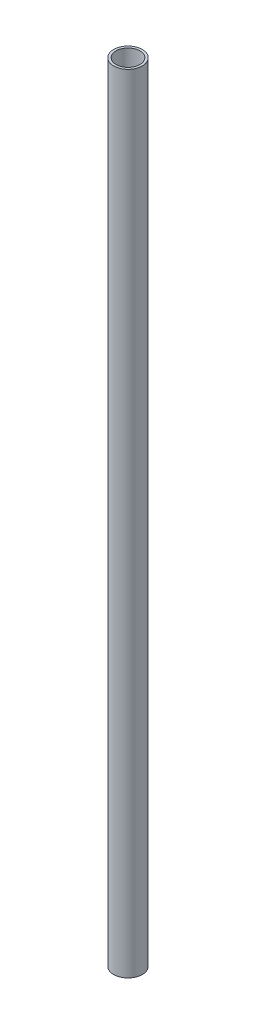
SolidWorks part; units mm, degrees
material "Thornel Mat VMA"
ref_plane "Front Plane" through (0, 0, 0) normal (0, 0, 1) x (1, 0, 0)
ref_plane "Top Plane" through (0, 0, 0) normal (0, 1, 0) x (1, 0, 0)
ref_plane "Right Plane" through (0, 0, 0) normal (1, 0, 0) x (0, 0, -1)
sketch "Sketch1" plane through (0, 0, 0) normal (0, 1, 0) x (1, 0, 0)
  circle A0 centre (0, 0) radius 6
  circle A1 centre (0, 0) radius 5
extrude "Boss-Extrude1" add sketch "Sketch1" along normal blind 330
